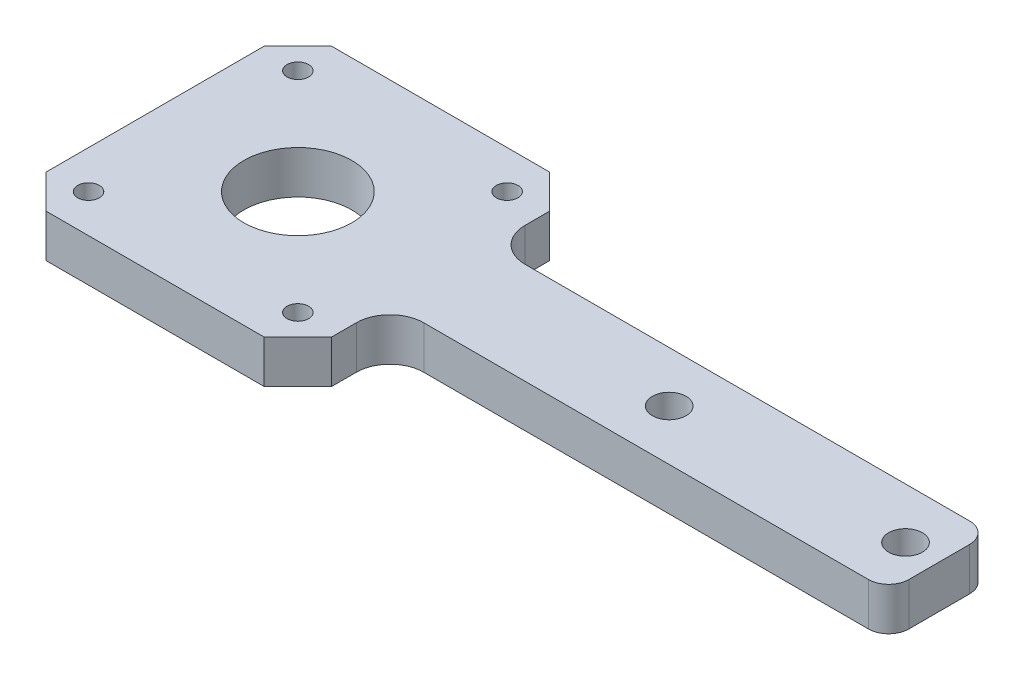
SolidWorks part; units mm, degrees
ref_plane "Front Plane" through (0, 0, 0) normal (0, 0, 1) x (1, 0, 0)
ref_plane "Top Plane" through (0, 0, 0) normal (0, 1, 0) x (1, 0, 0)
ref_plane "Right Plane" through (0, 0, 0) normal (1, 0, 0) x (0, 0, -1)
sketch "Sketch1" plane through (0, 0, 0) normal (0, 1, 0) x (1, 0, 0)
  line L0 (0, 0) -> (95, 0) construction
  line L1 (-15.5, 15.5) -> (15.5, 15.5) construction
  line L2 (-15.5, 15.5) -> (-15.5, -15.5) construction
  line L3 (-15.5, -15.5) -> (15.5, -15.5) construction
  line L4 (15.5, 15.5) -> (15.5, -15.5) construction
  line L5 (-15.5, 15.5) -> (15.5, -15.5) construction
  line L6 (-15.5, -15.5) -> (15.5, 15.5) construction
  line L7 (-21.15, 21.15) -> (21.15, 21.15)
  line L8 (-21.15, 21.15) -> (-21.15, -21.15)
  line L9 (-21.15, -21.15) -> (21.15, -21.15)
  line L11 (-21.15, 21.15) -> (21.15, -21.15) construction
  line L12 (-21.15, -21.15) -> (21.15, 21.15) construction
  line L13 (21.15, 7.5) -> (95, 7.5)
  line L14 (95, 7.5) -> (95, -7.5)
  line L15 (95, -7.5) -> (21.15, -7.5)
  line L16 (21.15, 21.15) -> (21.15, 7.5)
  line L17 (21.15, 7.5) -> (21.15, -7.5) construction
  line L18 (21.15, -7.5) -> (21.15, -21.15)
  circle A0 centre (-15.5, 15.5) radius 1.6
  circle A1 centre (15.5, 15.5) radius 1.6
  circle A2 centre (15.5, -15.5) radius 1.6
  circle A3 centre (-15.5, -15.5) radius 1.6
  circle A4 centre (0, 0) radius 8
  circle A5 centre (90, 0) radius 2.5
  circle A6 centre (55, 0) radius 2.5
  point P0 (0, 0)
  point P10 (0, 0)
  dimension "D2" = 3.2
  dimension "D4" = 16
  dimension "D9" = 5
  dimension "D1" = 31
  dimension "D3" = 42.3
  dimension "D5" = 15
  dimension "D6" = 95
  dimension "D7" = 5
  dimension "D8" = 35
extrude "Boss-Extrude2" add sketch "Sketch1" along normal blind 6.35
chamfer "Chamfer2" distance 5 angle 45 4 edges at (-21.15, 3.175, -21.15) (21.15, 3.175, -21.15) (21.15, 3.175, 21.15) (-21.15, 3.175, 21.15)
fillet "Fillet1" radius 3 2 edges at (95, 3.175, -7.5) (95, 3.175, 7.5)
fillet "Fillet2" radius 5 2 edges at (21.15, 3.175, -7.5) (21.15, 3.175, 7.5)
